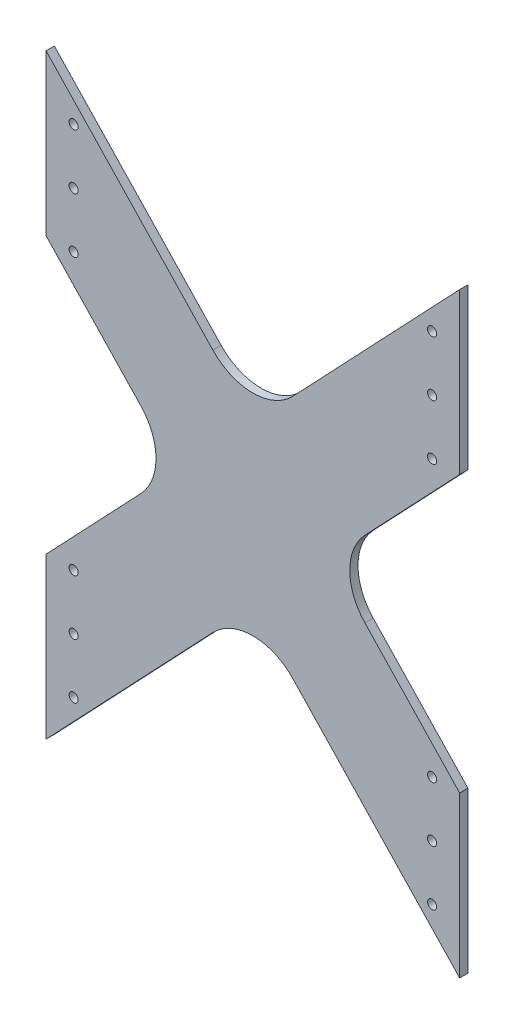
SolidWorks part; units mm, degrees
ref_plane "前视基准面" through (0, 0, 0) normal (0, 0, 1) x (1, 0, 0)
ref_plane "上视基准面" through (0, 0, 0) normal (0, 1, 0) x (1, 0, 0)
ref_plane "右视基准面" through (0, 0, 0) normal (1, 0, 0) x (0, 0, -1)
other "Configuration Table"
sketch "草图1" plane through (0, 0, 0) normal (0, 0, 1) x (1, 0, 0)
  line L1 (-81.16, 69.9779) -> (-33.7274, 19.978)
  line L3 (-81.161, -88.1418) -> (-81.1607, -30.0221)
  line L5 (-81.1596, 128.097) -> (-81.16, 69.9779)
  line L6 (-81.1607, -30.0221) -> (-33.7274, 19.978)
  line L7 (-81.161, -88.1418) -> (-6.1589, -9.0809)
  line L8 (-6.1589, 49.037) -> (-81.1596, 128.097)
  line L9 (-6.1597, -9.0817) -> (-6.1595, 49.0377) construction
  line L13 (-33.7274, 19.978) -> (21.4082, 19.9779) construction
  line L14 (-81.1607, -30.0221) -> (-71.1607, -30.0221) construction
  line L15 (68.8414, -88.1421) -> (68.8413, -30.0224)
  line L16 (68.8414, -88.1421) -> (-6.1604, -9.0809)
  line L17 (-6.1602, 49.037) -> (68.8409, 128.0968)
  line L18 (68.8413, -30.0224) -> (21.4082, 19.9779)
  line L19 (68.8409, 128.0968) -> (68.841, 69.9776)
  line L20 (68.841, 69.9776) -> (21.4082, 19.9779)
  circle A12 centre (-71.16, 69.9779) radius 1.65
  circle A13 centre (-71.1599, 89.9779) radius 1.65
  circle A14 centre (-71.1598, 109.9779) radius 1.65
  circle A15 centre (-71.1607, -30.0221) radius 1.65
  circle A16 centre (-71.1608, -50.0221) radius 1.65
  circle A17 centre (-71.1609, -70.0221) radius 1.65
  circle A18 centre (58.8414, -70.0224) radius 1.65
  circle A19 centre (58.8413, -50.0224) radius 1.65
  circle A20 centre (58.8413, -30.0224) radius 1.65
  circle A21 centre (58.8409, 109.9776) radius 1.65
  circle A22 centre (58.841, 89.9776) radius 1.65
  circle A23 centre (58.841, 69.9776) radius 1.65
  dimension "D12" = 3.3
  dimension "D13" = 10
  dimension "D14" = 10
  dimension "D10" = 3.3
  dimension "D11" = 3.3
  dimension "D18" = 3.3
  dimension "D19" = 3.3
  dimension "D20" = 3.3
  dimension "D1" = 40
  dimension "D3" = 100
  dimension "D6" = 108.9768
  dimension "D7" = 68.9197
  dimension "D8" = 68.9191
  dimension "D9" = 108.9753
  dimension "D15" = 10
  dimension "D16" = 20
  dimension "D17" = 20
  dimension "D21" = 10
  dimension "D22" = 10
  dimension "D23" = 10
  dimension "D24" = 20
  dimension "D25" = 20
extrude "凸台-拉伸1" add sketch "草图1" along normal blind 3
fillet "圆角1" radius 20 4 edges at (-33.7274, 19.978, 1.5) (-6.1597, -9.0817, 1.5) (21.4082, 19.9779, 1.5) (-6.1595, 49.0377, 1.5)
